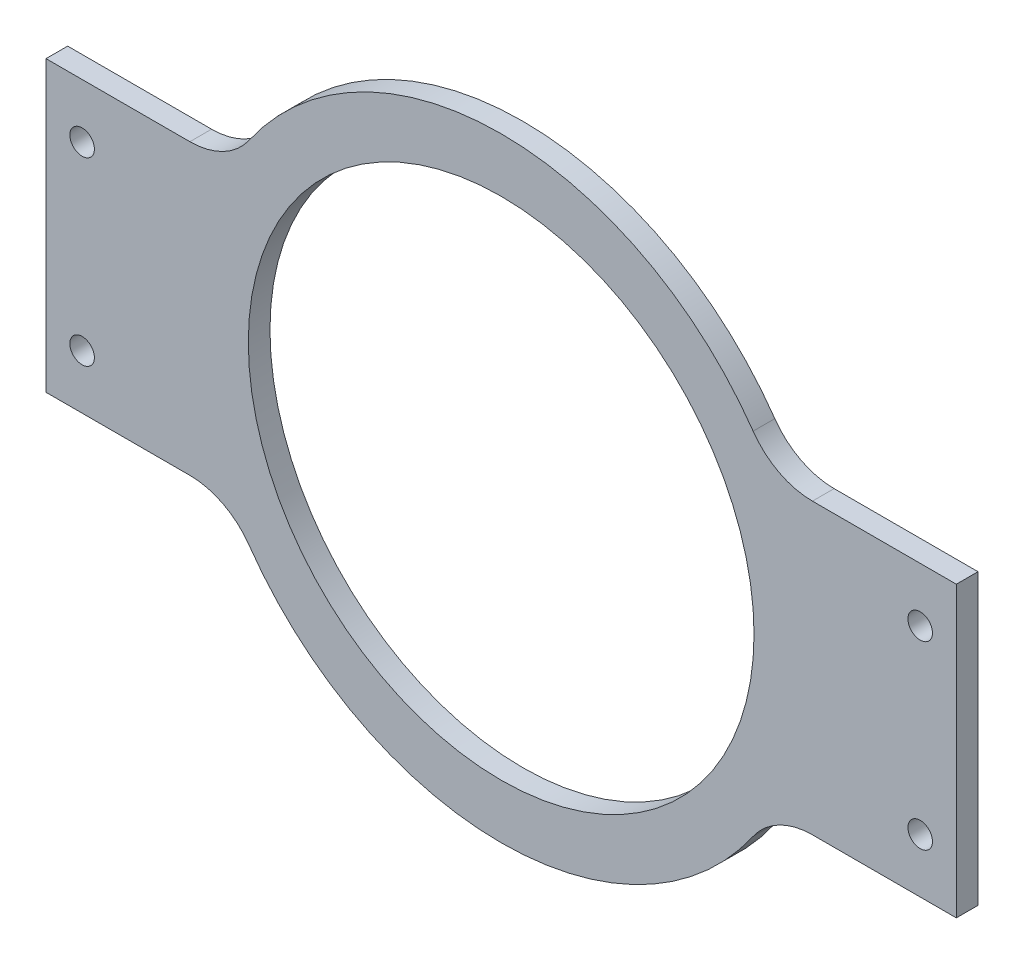
SolidWorks part; units mm, degrees
ref_plane "Front Plane" through (0, 0, 0) normal (0, 0, 1) x (1, 0, 0)
ref_plane "Top Plane" through (0, 0, 0) normal (0, 1, 0) x (1, 0, 0)
ref_plane "Right Plane" through (0, 0, 0) normal (1, 0, 0) x (0, 0, -1)
sketch "Sketch1" plane through (0, 0, 0) normal (0, 0, 1) x (1, 0, 0)
  line L0 (0, 0) -> (0, 60.9454) construction
  line L1 (-63, 20) -> (-37.5, 20)
  line L2 (-63, 20) -> (-63, -20)
  line L3 (-63, -20) -> (-37.5, -20)
  line L4 (63, 20) -> (63, -20)
  line L5 (0, 0) -> (90.607, 0) construction
  line L6 (37.5, 20) -> (63, 20)
  line L7 (37.5, -20) -> (63, -20)
  arc A0 (-37.5, -20) -> (37.5, -20) centre (0, 0) ccw
  arc A1 (37.5, 20) -> (-37.5, 20) centre (0, 0) ccw
  circle A2 centre (0, 0) radius 35
  point P7 (0, 60.9454)
  point P14 (90.607, 0)
  dimension "D1" = 85
  dimension "D4" = 70
  dimension "D2" = 126
  dimension "D3" = 40
extrude "Boss-Extrude1" add sketch "Sketch1" along normal mid plane 3
hole_wizard "M3 Clearance Hole1" positions "Sketch3" profile "Sketch2" hole size "M3" standard "ANSI Metric" end condition through all
sketch "Sketch3" plane through (0, 0, 1.5) normal (0, 0, 1) x (1, 0, 0)
  line L0 (0, 0) -> (-69.6822, 0) construction
  line L3 (-63, 20) -> (-63, -20) construction
  point P0 (-58, 12.5)
  point P2 (-58, -12.5)
  point P13 (0, 0)
  dimension "D1" = 5
  dimension "D2" = 25
sketch "Sketch2" plane through (-58, 12.5, 1.5) normal (1, 0, 0) x (0, -1, 0)
  line L0 (0, 0) -> (0, 3)
  line L1 (0, 3) -> (1.7, 3)
  line L2 (1.7, 3) -> (1.7, 0)
  line L5 (1.7, 0) -> (0, 0)
  line L11 (0, -6.35) -> (0, 107.95) construction
  dimension "Thru Hole Dia." = 3.4
  dimension "Thru Hole Depth" = 3
mirror "Mirror1" about plane through (0, 0, 0) normal (1, 0, 0) of "M3 Clearance Hole1"
fillet "Fillet1" radius 10 4 edges at (-37.5, -20, 0) (37.5, -20, 0) (37.5, 20, 0) (-37.5, 20, 0)
